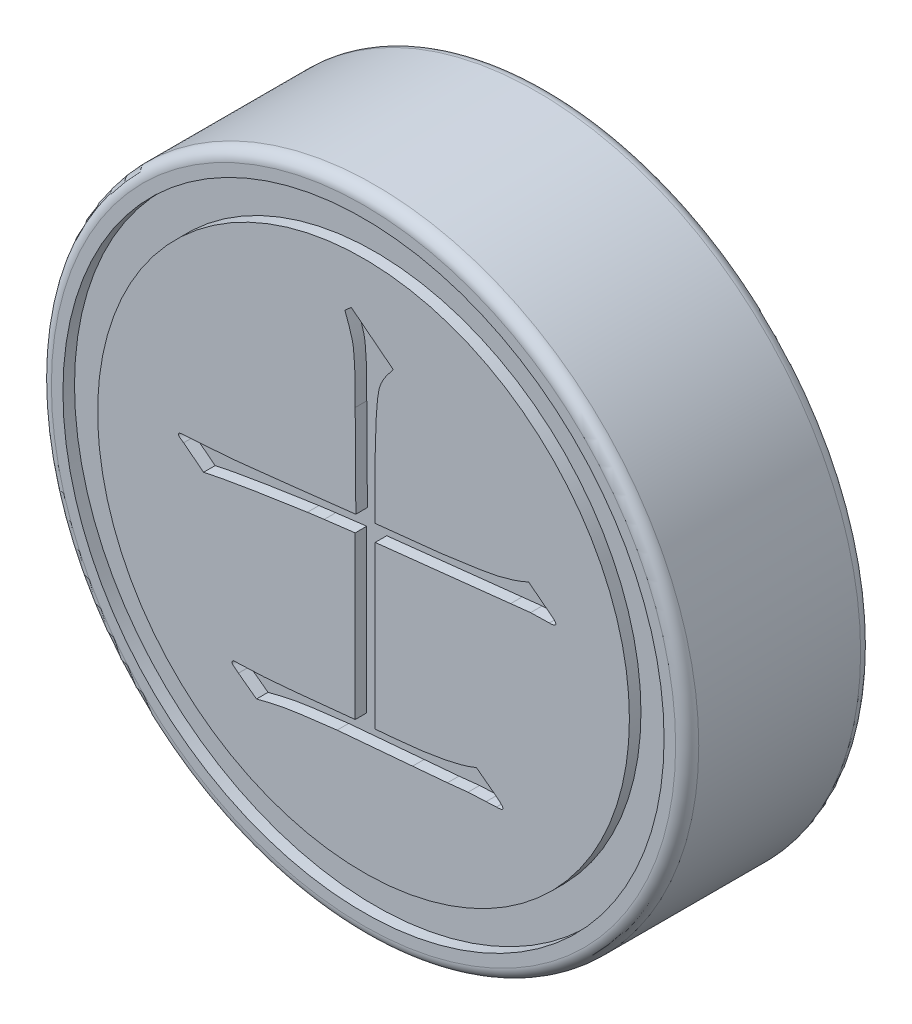
SolidWorks part; units mm, degrees
ref_plane "前视基准面" through (0, 0, 0) normal (0, 0, 1) x (1, 0, 0)
ref_plane "上视基准面" through (0, 0, 0) normal (0, 1, 0) x (1, 0, 0)
ref_plane "右视基准面" through (0, 0, 0) normal (1, 0, 0) x (0, 0, -1)
sketch "草图1" plane through (0, 0, 0) normal (0, 0, 1) x (1, 0, 0)
  circle A0 centre (0, 0) radius 14
extrude "凸台-拉伸1" add sketch "草图1" along normal blind 8
sketch "草图2" plane through (0, 0, 8) normal (0, 0, 1) x (1, 0, 0)
  circle A0 centre (0, 0) radius 13
  circle A1 centre (0, 0) radius 11.5
extrude "切除-拉伸1" cut sketch "草图2" against normal blind 0.5
sketch "草图3" plane through (0, 0, 0) normal (0, 0, -1) x (-1, 0, 0)
  circle A0 centre (0, 0) radius 5.1
extrude "切除-拉伸2" cut sketch "草图3" against normal blind 5
chamfer "倒角1" distance 0.5 angle 45 1 edges at (-5.1, 0, 0)
fillet "圆角1" radius 0.5 2 edges at (14, 0, 8) (14, 0, 0)
sketch "草图4" plane through (0, 0, 8) normal (0, 0, 1) x (1, 0, 0)
  text T0 "士" font "汉仪长仿宋体" height 13
extrude "切除-拉伸3" cut sketch "草图4" against normal blind 0.5
